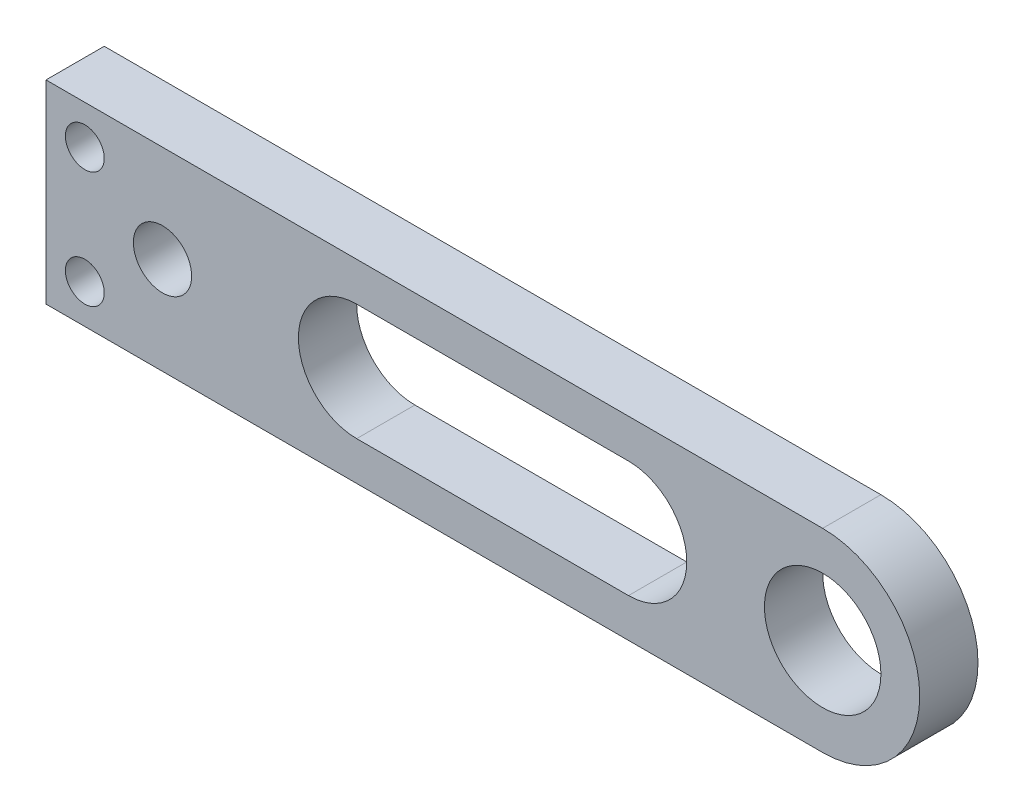
SolidWorks part; units mm, degrees
ref_plane "前视" through (0, 0, 0) normal (0, 0, 1) x (1, 0, 0)
ref_plane "上视" through (0, 0, 0) normal (0, 1, 0) x (1, 0, 0)
ref_plane "右视" through (0, 0, 0) normal (1, 0, 0) x (0, 0, -1)
sketch "草图2" plane through (0, 0, 0) normal (0, 0, 1) x (1, 0, 0)
  line L0 (0, 5) -> (34, 5)
  line L1 (0, -5) -> (34, -5)
  line L2 (10, 3) -> (24, 3)
  line L3 (10, -3) -> (24, -3)
  line L4 (-6, 0) -> (37.0477, 0) construction
  line L5 (0, 5) -> (-6, 5)
  line L6 (-6, 5) -> (-6, -5)
  line L7 (-6, -5) -> (0, -5)
  circle A0 centre (-4, 3) radius 1
  arc A1 (34, -5) -> (34, 5) centre (34, 0) ccw
  circle A2 centre (0, 0) radius 1.5
  circle A3 centre (34, 0) radius 3
  arc A4 (10, 3) -> (10, -3) centre (10, 0) ccw
  arc A5 (24, -3) -> (24, 3) centre (24, 0) ccw
  circle A6 centre (-4, -3) radius 1
  point P25 (-4.3042, 6)
  dimension "D1" = 6
  dimension "D2" = 10
  dimension "D3" = 3
  dimension "D4" = 6
  dimension "D8" = 6
  dimension "D9" = 6
  dimension "D12" = 2
  dimension "D15" = 2
  dimension "D5" = 34
  dimension "D6" = 10
  dimension "D7" = 10
  dimension "D10" = 2
  dimension "D11" = 2
  dimension "D13" = 2
  dimension "D14" = 2
extrude "凸台-拉伸1" add sketch "草图2" along normal blind 3
